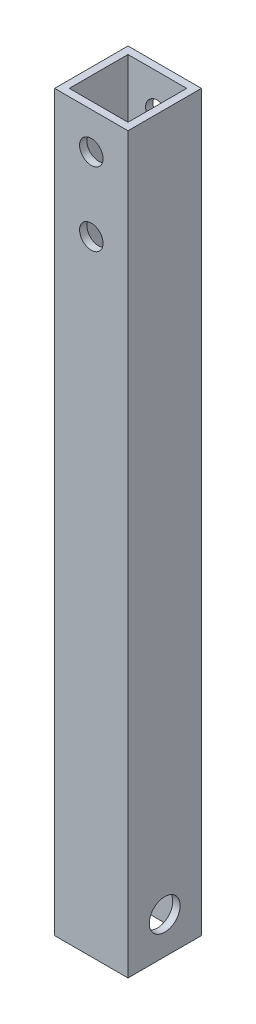
SolidWorks part; units mm, degrees
material "5052-H34"
ref_plane "正面" through (0, 0, 0) normal (0, 0, 1) x (1, 0, 0)
ref_plane "平面" through (0, 0, 0) normal (0, 1, 0) x (1, 0, 0)
ref_plane "右側面" through (0, 0, 0) normal (1, 0, 0) x (0, 0, -1)
sketch "ｽｹｯﾁ1" plane through (0, 0, 0) normal (0, 1, 0) x (1, 0, 0)
  line L1 (-5, 5) -> (5, 5)
  line L2 (-5, 5) -> (-5, -5)
  line L3 (-5, -5) -> (5, -5)
  line L4 (5, 5) -> (5, -5)
  line L5 (-5, 5) -> (5, -5) construction
  line L6 (-5, -5) -> (5, 5) construction
  point P0 (0, 0)
  dimension "D1" = 10
extrude "押し出し-薄板1" add sketch "ｽｹｯﾁ1" along normal blind 100 thin
sketch "ｽｹｯﾁ2" plane through (5, 0, 0) normal (1, 0, 0) x (0, 0, -1)
  line L0 (0, 0) -> (0, 5) construction
  circle A0 centre (0, 5) radius 2.1
  dimension "D1" = 4.2
  dimension "D2" = 5
extrude "ｶｯﾄ - 押し出し1" cut sketch "ｽｹｯﾁ2" against normal through all
sketch "ｽｹｯﾁ3" plane through (0, 0, 5) normal (0, 0, 1) x (1, 0, 0)
  line L0 (0, 100) -> (0, 85) construction
  line L1 (-5, 100) -> (5, 100) construction
  circle A0 centre (0, 85) radius 1.6
  circle A1 centre (0, 95) radius 1.6
  dimension "D1" = 3.2
  dimension "D2" = 10
  dimension "D3" = 5
extrude "ｶｯﾄ - 押し出し2" cut sketch "ｽｹｯﾁ3" against normal through all
